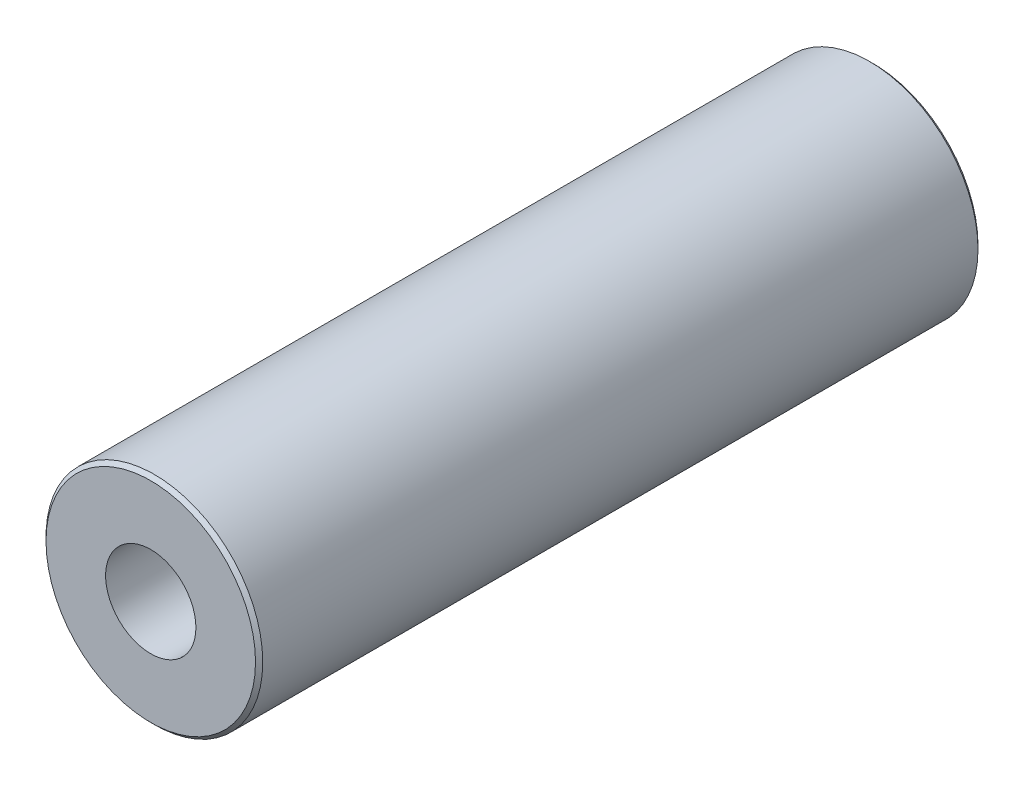
SolidWorks part; units mm, degrees
material "AISI 304"
ref_plane "前视基准面" through (0, 0, 0) normal (0, 0, 1) x (1, 0, 0)
ref_plane "上视基准面" through (0, 0, 0) normal (0, 1, 0) x (1, 0, 0)
ref_plane "右视基准面" through (0, 0, 0) normal (1, 0, 0) x (0, 0, -1)
sketch "草图1" plane through (0, 0, 0) normal (0, 0, 1) x (1, 0, 0)
  circle A0 centre (0, 0) radius 3
  dimension "D1" = 6
extrude "凸台-拉伸1" add sketch "草图1" along normal mid plane 20
chamfer "倒角1" distance 0.1 angle 45 2 edges at (3, 0, -10) (3, 0, 10)
hole_wizard "M3 螺纹孔1" positions "草图2" profile "草图3" tap size "M3" standard "GB" end condition through all
sketch "草图2" plane through (0, 0, 10) normal (0, 0, 1) x (1, 0, 0)
  point P0 (0, 0)
sketch "草图3" plane through (0, 0, 10) normal (1, 0, 0) x (0, -1, 0)
  line L0 (0, 0) -> (0, 20)
  line L1 (0, 20) -> (1.25, 20)
  line L2 (1.25, 20) -> (1.25, 0)
  line L5 (1.25, 0) -> (0, 0)
  line L11 (0, -6.35) -> (0, 107.95) construction
  dimension "通孔螺纹孔钻头直径" = 2.5
  dimension "通孔螺纹孔钻头深度" = 20
cosmetic thread "孔螺蚊线1" parameters "D2"=3
